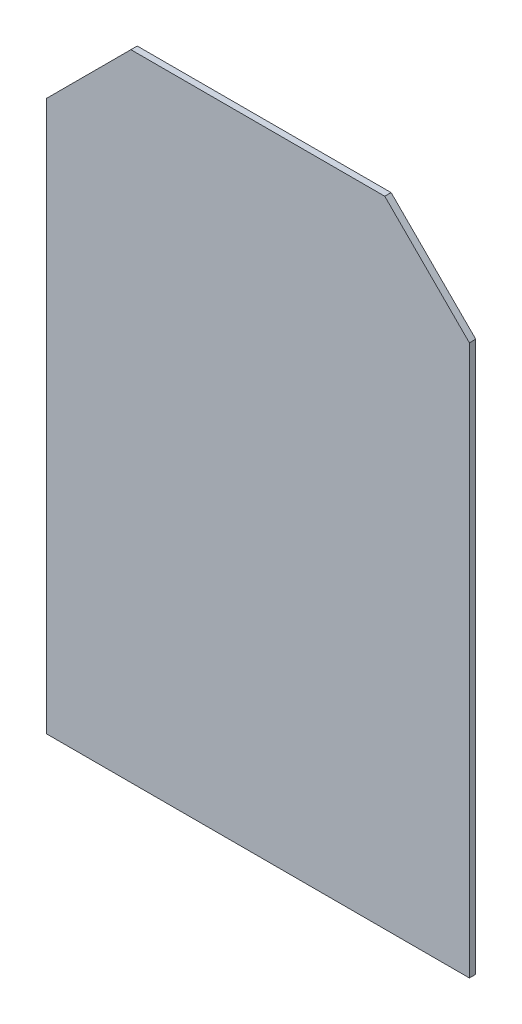
SolidWorks part; units mm, degrees
ref_plane "Front" through (0, 0, 0) normal (0, 0, 1) x (1, 0, 0)
ref_plane "Top" through (0, 0, 0) normal (0, 1, 0) x (1, 0, 0)
ref_plane "Right" through (0, 0, 0) normal (1, 0, 0) x (0, 0, -1)
sketch "草图1" plane through (0, 0, 0) normal (0, 0, 1) x (1, 0, 0)
  line L1 (-10, -15) -> (10, -15)
  line L2 (-10, -15) -> (-10, 15)
  line L3 (-10, 15) -> (10, 15)
  line L4 (10, -15) -> (10, 15)
  line L5 (-10, -15) -> (10, 15) construction
  line L6 (-10, 15) -> (10, -15) construction
  point P0 (0, 0)
  dimension "D1" = 20
  dimension "D2" = 30
extrude "凸台-拉伸1" add sketch "草图1" along normal blind 0.3
chamfer "倒角1" distance 4 angle 45 2 edges at (-10, 15, 0.15) (10, 15, 0.15)
